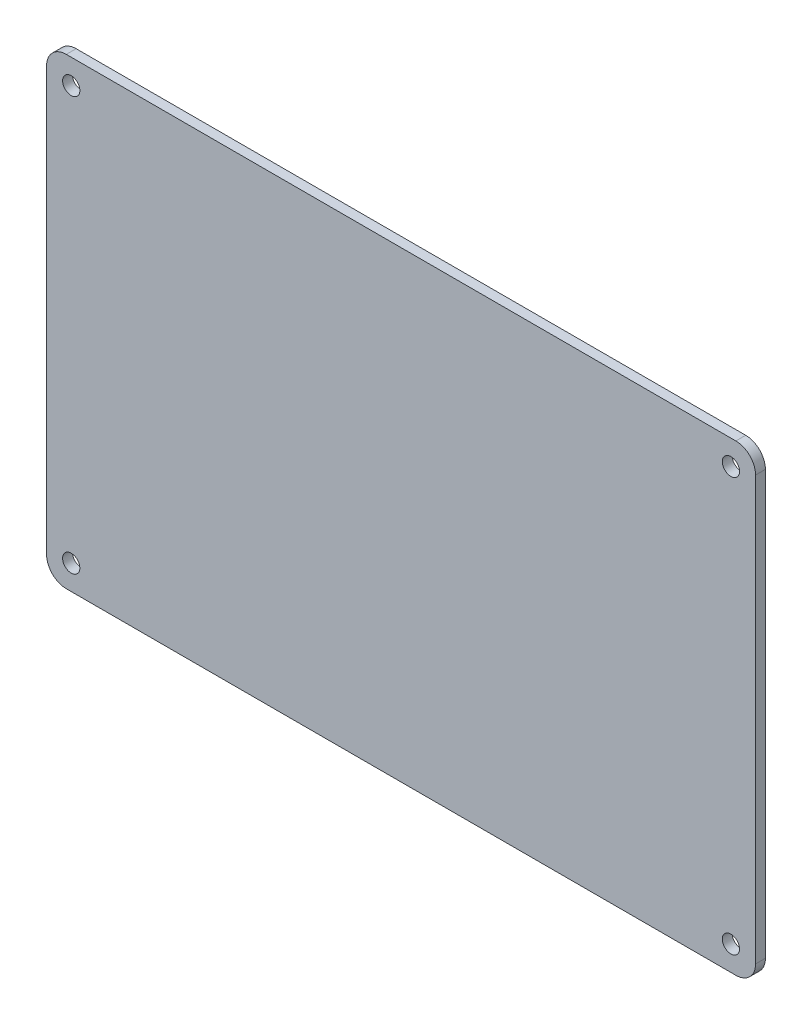
SolidWorks part; units mm, degrees
material "ABS"
ref_plane "Plano frontal" through (0, 0, 0) normal (0, 0, 1) x (1, 0, 0)
ref_plane "Plano superior" through (0, 0, 0) normal (0, 1, 0) x (1, 0, 0)
ref_plane "Plano direito" through (0, 0, 0) normal (1, 0, 0) x (0, 0, -1)
sketch "Esboço1" plane through (0, 0, 0) normal (0, 0, 1) x (1, 0, 0)
  line L0 (0, 0) -> (0, 61.3509) construction
  line L1 (-68, -47) -> (68, -47)
  line L2 (-72, -43) -> (-72, 43)
  line L3 (-68, 47) -> (68, 47)
  line L4 (72, -43) -> (72, 43)
  line L5 (-72, -47) -> (72, 47) construction
  line L6 (-72, 47) -> (72, -47) construction
  line L7 (0, 0) -> (51.0265, 0) construction
  arc A0 (68, 47) -> (72, 43) centre (68, 43) cw
  arc A1 (68, -47) -> (72, -43) centre (68, -43) ccw
  arc A2 (-68, -47) -> (-72, -43) centre (-68, -43) cw
  arc A3 (-72, 43) -> (-68, 47) centre (-68, 43) cw
  circle A4 centre (-67, 42) radius 1.75
  circle A5 centre (67, 42) radius 1.75
  circle A6 centre (-67, -42) radius 1.75
  circle A7 centre (67, -42) radius 1.75
  point P0 (0, 0)
  dimension "D3" = 4
  dimension "D4" = 84
  dimension "D5" = 134
  dimension "D6" = 3.5
  dimension "D1" = 94
  dimension "D2" = 144
extrude "Ressalto-extrusão1" add sketch "Esboço1" along normal blind 2
